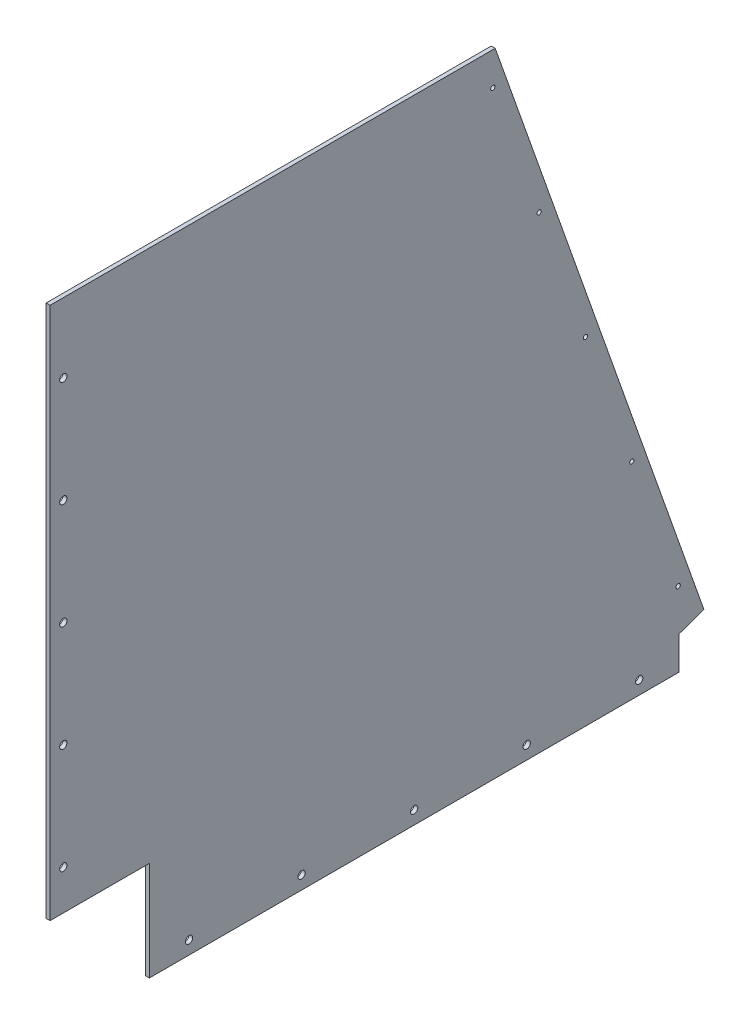
SolidWorks part; units mm, degrees
ref_plane "Front" through (0, 0, 0) normal (0, 0, 1) x (1, 0, 0)
ref_plane "Top" through (0, 0, 0) normal (0, 1, 0) x (1, 0, 0)
ref_plane "Right" through (0, 0, 0) normal (1, 0, 0) x (0, 0, -1)
sketch "Sketch1" plane through (0, 0, 0) normal (1, 0, 0) x (0, 0, -1)
  line L0 (31.6697, 625.5737) -> (191.6697, 173.0253)
  line L15 (-258.3303, 625.5737) -> (-258.3303, 173.0253)
  line L17 (-258.3303, 625.5737) -> (31.6697, 625.5737)
  line L18 (191.6697, 173.0253) -> (-258.3303, 173.0253)
  circle A0 centre (31.6697, 625.5737) radius 480 construction
  dimension "D3" = 450
  dimension "D1" = 480
  dimension "D2" = 452.5483
  dimension "D4" = 290
extrude "Boss-Extrude1" add sketch "Sketch1" along normal blind 3
sketch "Sketch2" plane through (0, 0, 0) normal (-1, 0, 0) x (0, 0, 1)
  line L1 (258.3303, 173.0253) -> (208.3303, 173.0253)
  line L2 (258.3303, 173.0253) -> (258.3303, 223.0253)
  line L3 (258.3303, 223.0253) -> (208.3303, 223.0253)
  line L4 (208.3303, 173.0253) -> (208.3303, 223.0253)
  dimension "D1" = 50
  dimension "D2" = 50
extrude "Cut-Extrude1" cut sketch "Sketch2" against normal blind 10
sketch "Sketch3" plane through (0, 79.461, -224.7497) normal (0, 0.3333, -0.9428) x (-1, 0, 0)
  line L1 (-3, 579.24) -> (0, 579.24)
  line L2 (-3, 579.24) -> (-3, 99.24)
  line L3 (-3, 99.24) -> (0, 99.24)
  line L4 (0, 579.24) -> (0, 99.24)
extrude "Boss-Extrude2" add sketch "Sketch3" along normal blind 20
ref_plane "Plane1" through (3, 173.0253, 208.3303) normal (0, 0, -1) x (-1, 0, 0)
sketch "Sketch5" plane through (0, 173.0253, 0) normal (0, -1, 0) x (1, 0, 0)
  line L1 (3, 208.3303) -> (0, 208.3303)
  line L2 (3, 208.3303) -> (3, -191.6697)
  line L3 (3, -191.6697) -> (0, -191.6697)
  line L4 (0, 208.3303) -> (0, -191.6697)
extrude "Boss-Extrude3" add sketch "Sketch5" along normal blind 25
sketch "Sketch6" plane through (0, 0, 258.3303) normal (0, 0, 1) x (1, 0, 0)
  line L1 (0, 625.5737) -> (3, 625.5737)
  line L2 (0, 625.5737) -> (0, 223.0253)
  line L3 (0, 223.0253) -> (3, 223.0253)
  line L4 (3, 625.5737) -> (3, 223.0253)
extrude "Boss-Extrude4" add sketch "Sketch6" along normal blind 25
sketch "Sketch7" plane through (3, 0, 0) normal (1, 0, 0) x (0, 0, -1)
  line L1 (31.6697, 625.5737) -> (56.8706, 625.5737)
  line L2 (31.6697, 625.5737) -> (31.6697, 639.891)
  line L3 (31.6697, 639.891) -> (56.8706, 639.891)
  line L4 (56.8706, 625.5737) -> (56.8706, 639.891)
extrude "Cut-Extrude2" cut sketch "Sketch7" against normal blind 25
hole_wizard "Ø3.2 (3.2) Diameter Hole1" positions "Sketch8" profile "Sketch9" hole size "Ø3.2" standard "DIN" end condition up to next
sketch "Sketch8" plane through (3, 0, 0) normal (1, 0, 0) x (0, 0, -1)
  line L0 (52.8829, 625.5737) -> (210.5258, 179.692) construction
  line L1 (210.5258, 179.692) -> (191.6697, 173.0253) construction
  point P0 (191.0978, 204.6429)
  point P19 (156.0978, 303.6379)
  point P20 (121.0978, 402.6328)
  point P21 (86.0978, 501.6278)
  point P22 (51.0978, 600.6227)
  dimension "D1" = 10
  dimension "D2" = 30
  dimension "D3" = 5
sketch "Sketch9" plane through (3, 204.6429, -191.0978) normal (0, 1, 0) x (0, 0, -1)
  line L0 (0, 0) -> (0, 3)
  line L1 (0, 3) -> (1.6, 3)
  line L2 (1.6, 3) -> (1.6, 0)
  line L5 (1.6, 0) -> (0, 0)
  line L11 (0, -6.35) -> (0, 107.95) construction
  dimension "Thru Hole Dia." = 3.2
  dimension "Thru Hole Depth" = 3
hole_wizard "Ø5.5 (5.5) Diameter Hole1" positions "Sketch10" profile "Sketch11" hole size "Ø5.5" standard "DIN" end condition up to next
sketch "Sketch10" plane through (3, 0, 0) normal (1, 0, 0) x (0, 0, -1)
  line L0 (191.6697, 148.0253) -> (-208.3303, 148.0253) construction
  line L1 (191.6697, 148.0253) -> (191.6697, 173.0253) construction
  line L2 (-208.3303, 223.0253) -> (-208.3303, 148.0253) construction
  line L3 (-283.3303, 223.0253) -> (-283.3303, 625.5737) construction
  line L4 (-283.3303, 223.0253) -> (-208.3303, 223.0253) construction
  point P0 (161.6697, 158.0253)
  point P11 (76.6697, 158.0253)
  point P12 (-8.3303, 158.0253)
  point P13 (-93.3303, 158.0253)
  point P14 (-178.3303, 158.0253)
  point P17 (-273.3303, 253.0253)
  point P28 (-273.3303, 333.0253)
  point P29 (-273.3303, 413.0253)
  point P30 (-273.3303, 493.0253)
  point P31 (-273.3303, 573.0253)
  dimension "D1" = 10
  dimension "D2" = 30
  dimension "D4" = 30
  dimension "D5" = 10
  dimension "D6" = 30
  dimension "D8" = 80
  dimension "D3" = 5
  dimension "D7" = 5
sketch "Sketch11" plane through (3, 158.0253, -161.6697) normal (0, 1, 0) x (0, 0, -1)
  line L0 (0, 0) -> (0, 3)
  line L1 (0, 3) -> (2.75, 3)
  line L2 (2.75, 3) -> (2.75, 0)
  line L5 (2.75, 0) -> (0, 0)
  line L11 (0, -6.35) -> (0, 107.95) construction
  dimension "Thru Hole Dia." = 5.5
  dimension "Thru Hole Depth" = 3
